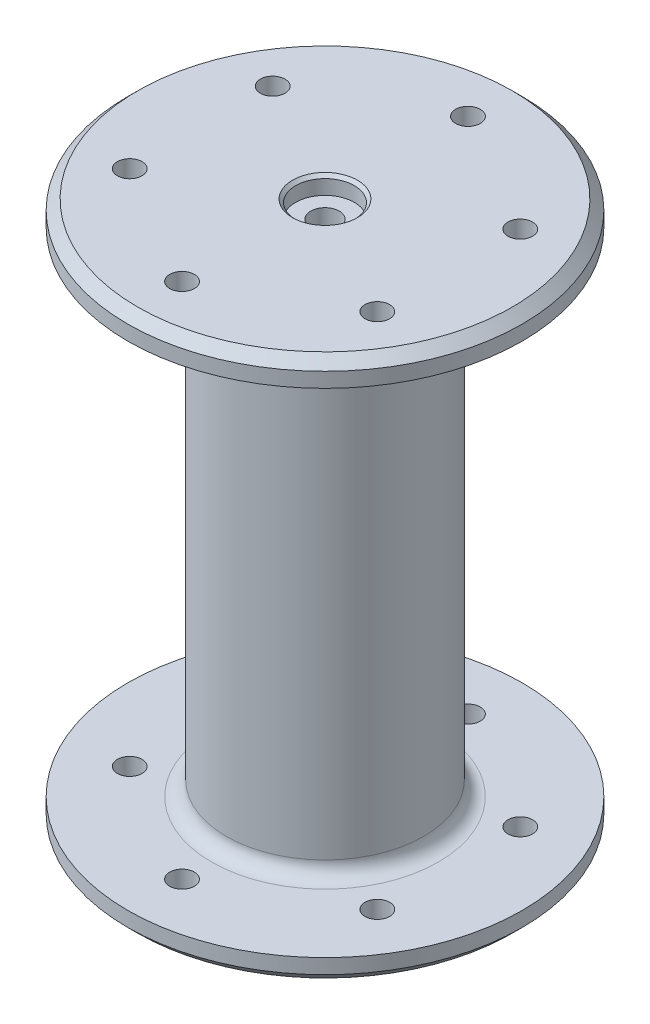
SolidWorks part; units mm, degrees
ref_plane "Front Plane" through (0, 0, 0) normal (0, 0, 1) x (1, 0, 0)
ref_plane "Top Plane" through (0, 0, 0) normal (0, 1, 0) x (1, 0, 0)
ref_plane "Right Plane" through (0, 0, 0) normal (1, 0, 0) x (0, 0, -1)
sketch "Sketch1" plane through (0, 0, 0) normal (0, 1, 0) x (1, 0, 0)
  circle A0 centre (0, 0) radius 20
  dimension "ShaftDiameter" = 40
extrude "Boss-Extrude1" add sketch "Sketch1" along normal mid plane 100
sketch "Sketch2" plane through (0, 50, 0) normal (0, 1, 0) x (1, 0, 0)
  circle A0 centre (0, 0) radius 40
  dimension "CapDiameter" = 80
extrude "Boss-Extrude2" add sketch "Sketch2" along normal blind 5
chamfer "Chamfer1" distance 2 angle 45 1 edges at (0, 55, 40)
sketch "Sketch3" plane through (0, 55, 0) normal (0, 1, 0) x (1, 0, 0)
  line L0 (0, 20) -> (0, 38) construction
  circle A0 centre (0, 0) radius 20 construction
  circle A1 centre (0, 0) radius 38 construction
  circle A2 centre (0, 29) radius 2.5
  dimension "D1" = 5
extrude "Cut-Extrude1" cut sketch "Sketch3" against normal through all
pattern_circular "CirPattern1" count 6 over 360 about axis through (0, 0, 0) along (0, 1, 0) of "Cut-Extrude1"
fillet "Fillet4" radius 3 1 edges at (0, 50, 20)
hole_wizard "CBORE for #12 Binding Head Machine Screw1" positions "Sketch4" profile "Sketch5" counterbore size "#12" standard "ANSI Inch" end condition through all
sketch "Sketch4" plane through (0, 55, 0) normal (0, 1, 0) x (1, 0, 0)
  point P0 (0, 0)
sketch "Sketch5" plane through (0, 55, 0) normal (1, 0, 0) x (0, 0, 1)
  line L0 (0, 0) -> (0, 110)
  line L1 (0, 110) -> (2.8956, 110)
  line L3 (2.8956, 110) -> (2.8956, 3.5814)
  line L4 (5.9538, 3.5814) -> (2.8956, 3.5814)
  line L5 (5.9538, 3.5814) -> (5.9538, 0.635)
  line L6 (5.9538, 0.635) -> (6.5888, 0)
  line L7 (6.5888, 0) -> (0, 0)
  line L8 (-5.9538, 0.635) -> (-6.5888, 0) construction
  line L11 (0, -6.35) -> (0, 107.95) construction
  dimension "Thru Hole Dia." = 5.7912
  dimension "Thru Hole Depth" = 110
  dimension "C'Bore Dia." = 11.9075
  dimension "C'Bore Depth" = 3.5814
  dimension "Near C'Sink Dia." = 13.1775
  dimension "Near C'Sink Angle" = 90
mirror "Mirror1" about plane through (0, 0, 0) normal (0, 1, 0) of "Boss-Extrude2", "Chamfer1", "CirPattern1", "Cut-Extrude1", "Fillet4", "CBORE for #12 Binding Head Machine Screw1"
